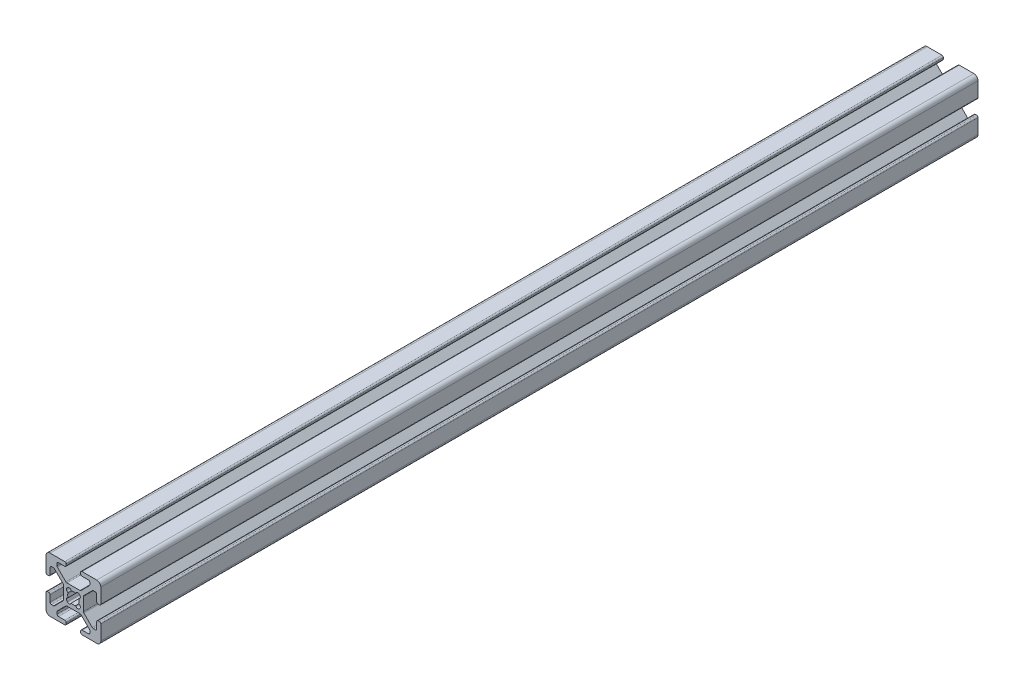
SolidWorks part; units mm, degrees
material "Alumina"
ref_plane "Front Plane" through (0, 0, 0) normal (0, 0, 1) x (1, 0, 0)
ref_plane "Top Plane" through (0, 0, 0) normal (0, 1, 0) x (1, 0, 0)
ref_plane "Right Plane" through (0, 0, 0) normal (1, 0, 0) x (0, 0, -1)
ref_plane "Plane1" through (0, 0, 4000) normal (0, 0, 1) x (1, 0, 0)
sketch "Sketch1" plane through (0, 0, 4000) normal (0, 0, 1) x (1, 0, 0)
  line B0 (10, 3.138) -> (10, 8.5)
  line B1 (8.5, 10) -> (3.138, 10)
  line B2 (2.63, 9.492) -> (2.63, 9.008)
  line B3 (3.138, 8.5) -> (5.487, 8.5)
  line B4 (5.995, 7.992) -> (5.995, 7.2661)
  line B5 (5.8462, 6.9069) -> (2.7431, 3.8038)
  line B6 (2.3839, 3.655) -> (-2.3839, 3.655)
  line B7 (-2.7431, 3.8038) -> (-5.8462, 6.9069)
  line B8 (-5.995, 7.2661) -> (-5.995, 7.992)
  line B9 (-5.487, 8.5) -> (-3.138, 8.5)
  line B10 (-2.63, 9.008) -> (-2.63, 9.492)
  line B11 (-3.138, 10) -> (-8.5, 10)
  line B12 (-10, 8.5) -> (-10, 3.138)
  line B13 (-9.492, 2.63) -> (-9.008, 2.63)
  line B14 (-8.5, 3.138) -> (-8.5, 5.487)
  line B15 (-7.992, 5.995) -> (-7.2661, 5.995)
  line B16 (-6.9069, 5.8462) -> (-3.8038, 2.7431)
  line B17 (-3.655, 2.3839) -> (-3.655, -2.3839)
  line B18 (-3.8038, -2.7431) -> (-6.9069, -5.8462)
  line B19 (-7.2661, -5.995) -> (-7.992, -5.995)
  line B20 (-8.5, -5.487) -> (-8.5, -3.138)
  line B21 (-9.008, -2.63) -> (-9.492, -2.63)
  line B22 (-10, -3.138) -> (-10, -8.5)
  line B23 (-8.5, -10) -> (-3.138, -10)
  line B24 (-2.63, -9.492) -> (-2.63, -9.008)
  line B25 (-3.138, -8.5) -> (-5.487, -8.5)
  line B26 (-5.995, -7.992) -> (-5.995, -7.2661)
  line B27 (-5.8462, -6.9069) -> (-2.7431, -3.8038)
  line B28 (-2.3839, -3.655) -> (2.3839, -3.655)
  line B29 (2.7431, -3.8038) -> (5.8462, -6.9069)
  line B30 (5.995, -7.2661) -> (5.995, -7.992)
  line B31 (5.487, -8.5) -> (3.138, -8.5)
  line B32 (2.63, -9.008) -> (2.63, -9.492)
  line B33 (3.138, -10) -> (8.5, -10)
  line B34 (10, -8.5) -> (10, -3.138)
  line B35 (9.492, -2.63) -> (9.008, -2.63)
  line B36 (8.5, -3.138) -> (8.5, -5.487)
  line B37 (7.992, -5.995) -> (7.2661, -5.995)
  line B38 (6.9069, -5.8462) -> (3.8038, -2.7431)
  line B39 (3.655, -2.3839) -> (3.655, 2.3839)
  line B40 (3.8038, 2.7431) -> (6.9069, 5.8462)
  line B41 (7.2661, 5.995) -> (7.992, 5.995)
  line B42 (8.5, 5.487) -> (8.5, 3.138)
  line B43 (9.008, 2.63) -> (9.492, 2.63)
  line B44 (-2.1249, -2.3045) -> (-2.3045, -2.1249)
  line B45 (-2.3045, 2.1249) -> (-2.1249, 2.3045)
  line B46 (2.1249, 2.3045) -> (2.3045, 2.1249)
  line B47 (2.3045, -2.1249) -> (2.1249, -2.3045)
  arc B48 (9.492, 2.63) -> (10, 3.138) centre (9.492, 3.138) ccw
  arc B49 (10, 8.5) -> (8.5, 10) centre (8.5, 8.5) ccw
  arc B50 (3.138, 10) -> (2.63, 9.492) centre (3.138, 9.492) ccw
  arc B51 (2.63, 9.008) -> (3.138, 8.5) centre (3.138, 9.008) ccw
  arc B52 (5.487, 8.5) -> (5.995, 7.992) centre (5.487, 7.992) cw
  arc B53 (5.995, 7.2661) -> (5.8462, 6.9069) centre (5.487, 7.2661) cw
  arc B54 (2.7431, 3.8038) -> (2.3839, 3.655) centre (2.3839, 4.163) cw
  arc B55 (-2.3839, 3.655) -> (-2.7431, 3.8038) centre (-2.3839, 4.163) cw
  arc B56 (-5.8462, 6.9069) -> (-5.995, 7.2661) centre (-5.487, 7.2661) cw
  arc B57 (-5.995, 7.992) -> (-5.487, 8.5) centre (-5.487, 7.992) cw
  arc B58 (-3.138, 8.5) -> (-2.63, 9.008) centre (-3.138, 9.008) ccw
  arc B59 (-2.63, 9.492) -> (-3.138, 10) centre (-3.138, 9.492) ccw
  arc B60 (-8.5, 10) -> (-10, 8.5) centre (-8.5, 8.5) ccw
  arc B61 (-10, 3.138) -> (-9.492, 2.63) centre (-9.492, 3.138) ccw
  arc B62 (-9.008, 2.63) -> (-8.5, 3.138) centre (-9.008, 3.138) ccw
  arc B63 (-8.5, 5.487) -> (-7.992, 5.995) centre (-7.992, 5.487) cw
  arc B64 (-7.2661, 5.995) -> (-6.9069, 5.8462) centre (-7.2661, 5.487) cw
  arc B65 (-3.8038, 2.7431) -> (-3.655, 2.3839) centre (-4.163, 2.3839) cw
  arc B66 (-3.655, -2.3839) -> (-3.8038, -2.7431) centre (-4.163, -2.3839) cw
  arc B67 (-6.9069, -5.8462) -> (-7.2661, -5.995) centre (-7.2661, -5.487) cw
  arc B68 (-7.992, -5.995) -> (-8.5, -5.487) centre (-7.992, -5.487) cw
  arc B69 (-8.5, -3.138) -> (-9.008, -2.63) centre (-9.008, -3.138) ccw
  arc B70 (-9.492, -2.63) -> (-10, -3.138) centre (-9.492, -3.138) ccw
  arc B71 (-10, -8.5) -> (-8.5, -10) centre (-8.5, -8.5) ccw
  arc B72 (-3.138, -10) -> (-2.63, -9.492) centre (-3.138, -9.492) ccw
  arc B73 (-2.63, -9.008) -> (-3.138, -8.5) centre (-3.138, -9.008) ccw
  arc B74 (-5.487, -8.5) -> (-5.995, -7.992) centre (-5.487, -7.992) cw
  arc B75 (-5.995, -7.2661) -> (-5.8462, -6.9069) centre (-5.487, -7.2661) cw
  arc B76 (-2.7431, -3.8038) -> (-2.3839, -3.655) centre (-2.3839, -4.163) cw
  arc B77 (2.3839, -3.655) -> (2.7431, -3.8038) centre (2.3839, -4.163) cw
  arc B78 (5.8462, -6.9069) -> (5.995, -7.2661) centre (5.487, -7.2661) cw
  arc B79 (5.995, -7.992) -> (5.487, -8.5) centre (5.487, -7.992) cw
  arc B80 (3.138, -8.5) -> (2.63, -9.008) centre (3.138, -9.008) ccw
  arc B81 (2.63, -9.492) -> (3.138, -10) centre (3.138, -9.492) ccw
  arc B82 (8.5, -10) -> (10, -8.5) centre (8.5, -8.5) ccw
  arc B83 (10, -3.138) -> (9.492, -2.63) centre (9.492, -3.138) ccw
  arc B84 (9.008, -2.63) -> (8.5, -3.138) centre (9.008, -3.138) ccw
  arc B85 (8.5, -5.487) -> (7.992, -5.995) centre (7.992, -5.487) cw
  arc B86 (7.2661, -5.995) -> (6.9069, -5.8462) centre (7.2661, -5.487) cw
  arc B87 (3.8038, -2.7431) -> (3.655, -2.3839) centre (4.163, -2.3839) cw
  arc B88 (3.655, 2.3839) -> (3.8038, 2.7431) centre (4.163, 2.3839) cw
  arc B89 (6.9069, 5.8462) -> (7.2661, 5.995) centre (7.2661, 5.487) cw
  arc B90 (7.992, 5.995) -> (8.5, 5.487) centre (7.992, 5.487) cw
  arc B91 (8.5, 3.138) -> (9.008, 2.63) centre (9.008, 3.138) ccw
  arc B92 (0.804, -1.9351) -> (-0.804, -1.9351) centre (0, 0) cw
  arc B93 (-0.804, -1.9351) -> (-2.1249, -2.3045) centre (-1.5684, -1.748) cw
  arc B94 (-2.3045, -2.1249) -> (-1.9351, -0.804) centre (-1.748, -1.5684) cw
  arc B95 (-1.9351, -0.804) -> (-1.9351, 0.804) centre (0, 0) cw
  arc B96 (-1.9351, 0.804) -> (-2.3045, 2.1249) centre (-1.748, 1.5684) cw
  arc B97 (-2.1249, 2.3045) -> (-0.804, 1.9351) centre (-1.5684, 1.748) cw
  arc B98 (-0.804, 1.9351) -> (0.804, 1.9351) centre (0, 0) cw
  arc B99 (0.804, 1.9351) -> (2.1249, 2.3045) centre (1.5684, 1.748) cw
  arc B100 (2.3045, 2.1249) -> (1.9351, 0.804) centre (1.748, 1.5684) cw
  arc B101 (1.9351, 0.804) -> (1.9351, -0.804) centre (0, 0) cw
  arc B102 (1.9351, -0.804) -> (2.3045, -2.1249) centre (1.748, -1.5684) cw
  arc B103 (2.1249, -2.3045) -> (0.804, -1.9351) centre (1.5684, -1.748) cw
sketch_block_instance "Block1-1"
sketch_block "Block1"
extrude "Boss-Extrude1" add sketch "Sketch1" against normal blind 320
